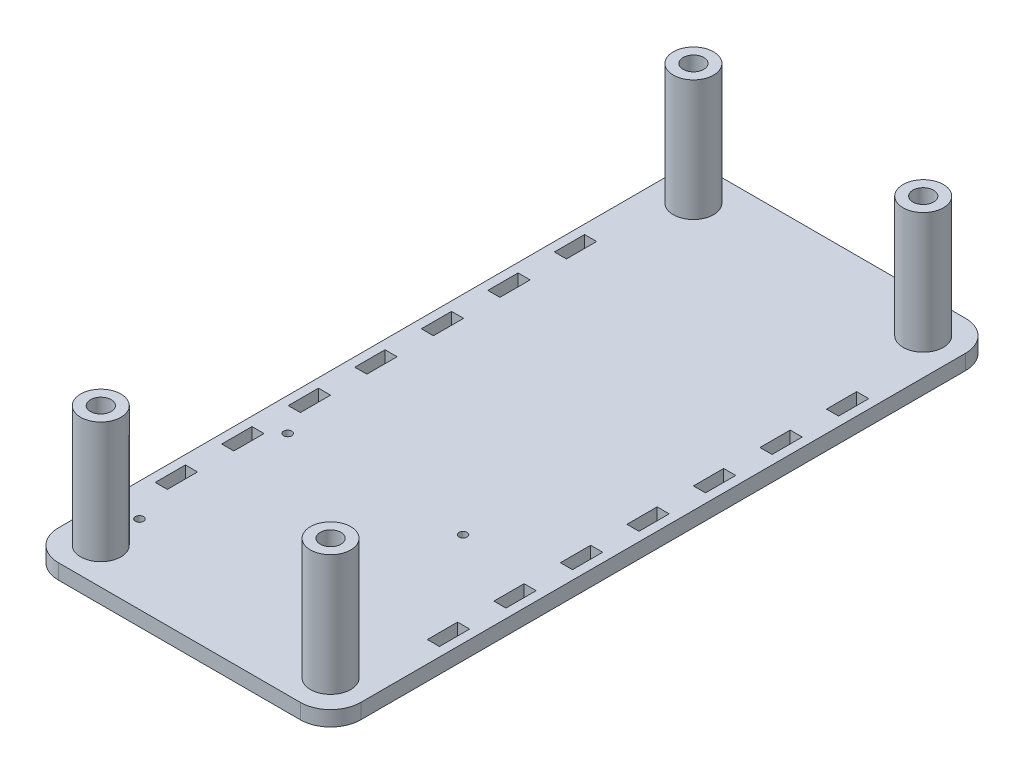
SolidWorks part; units mm, degrees
ref_plane "Front Plane" through (0, 0, 0) normal (0, 0, 1) x (1, 0, 0)
ref_plane "Top Plane" through (0, 0, 0) normal (0, 1, 0) x (1, 0, 0)
ref_plane "Right Plane" through (0, 0, 0) normal (1, 0, 0) x (0, 0, -1)
sketch "Sketch1" plane through (0, 0, 0) normal (0, 1, 0) x (1, 0, 0)
  line L2 (-104.5, 110) -> (-4.5, 110)
  line L5 (-104.5, 110) -> (-104.5, -110)
  line L6 (-104.5, -110) -> (-4.5, -110)
  line L7 (-4.5, 110) -> (-4.5, -110)
  point P6 (-54.5, 110)
  dimension "D1" = 220
  dimension "D2" = 100
extrude "Boss-Extrude1" add sketch "Sketch1" along normal blind 5
fillet "Fillet1" radius 10 1 edges at (-4.5, 2.5, 110)
fillet "Fillet2" radius 10 1 edges at (-4.5, 2.5, -110)
fillet "Fillet3" radius 10 1 edges at (-104.5, 2.5, 110)
fillet "Fillet4" radius 10 1 edges at (-104.5, 2.5, -110)
sketch "Sketch2" plane through (0, 5, 0) normal (0, 1, 0) x (1, 0, 0)
  circle A0 centre (-92.5, 98) radius 6.6681
  circle A1 centre (-92.5, -98) radius 6.6681
  circle A2 centre (-16.5, 98) radius 6.6681
  circle A3 centre (-16.5, -98) radius 6.6681
  point P17 (-54.5, 0)
extrude "Boss-Extrude2" add sketch "Sketch2" along normal blind 40
sketch "Sketch4" plane through (0, 45, 0) normal (0, 1, 0) x (1, 0, 0)
  circle A2 centre (-92.5, 98) radius 3.4181
  circle A3 centre (-92.5, 98) radius 3.4181
  dimension "D1" = 3.25
extrude "Cut-Extrude1" cut sketch "Sketch4" against normal blind 15
sketch "Sketch5" plane through (0, 45, 0) normal (0, 1, 0) x (1, 0, 0)
  circle A2 centre (-92.5, -98) radius 3.4181
  circle A3 centre (-92.5, -98) radius 3.4181
  dimension "D1" = 3.25
extrude "Cut-Extrude2" cut sketch "Sketch5" against normal blind 15
sketch "Sketch6" plane through (0, 45, 0) normal (0, 1, 0) x (1, 0, 0)
  circle A2 centre (-16.5, 98) radius 3.4181
  circle A3 centre (-16.5, 98) radius 3.4181
  dimension "D1" = 3.25
extrude "Cut-Extrude3" cut sketch "Sketch6" against normal blind 15
sketch "Sketch7" plane through (0, 45, 0) normal (0, 1, 0) x (1, 0, 0)
  circle A2 centre (-16.5, -98) radius 3.4181
  circle A3 centre (-16.5, -98) radius 3.4181
  dimension "D1" = 3.25
extrude "Cut-Extrude4" cut sketch "Sketch7" against normal blind 15
sketch "Sketch8" plane through (0, 5, 0) normal (0, 1, 0) x (1, 0, 0)
  line L0 (-7.5, -71) -> (-11.5, -71) construction
  line L1 (-24.75, 0) -> (24.75, 0) construction
  line L2 (-11.5, -71) -> (-11.5, -61) construction
  line L3 (-7.5, 5) -> (-11.5, 5) construction
  line L9 (-101.5, 71) -> (-97.5, 71) construction
  line L14 (-97.5, 71) -> (-97.5, 61) construction
  line L15 (-7.5, -5) -> (-11.5, -5) construction
  line L19 (-101.5, 71) -> (-97.5, 71)
  line L20 (-101.5, 71) -> (-101.5, 61)
  line L21 (-101.5, 61) -> (-97.5, 61)
  line L22 (-97.5, 71) -> (-97.5, 61)
  line L24 (-101.5, 49) -> (-97.5, 49)
  line L25 (-97.5, 39) -> (-97.5, 49)
  line L26 (-101.5, 39) -> (-97.5, 39)
  line L27 (-101.5, 39) -> (-101.5, 49)
  line L28 (-11.5, -5) -> (-11.5, 5) construction
  line L33 (-97.5, -5) -> (-97.5, 5) construction
  line L34 (-101.5, -5) -> (-97.5, -5) construction
  line L37 (-101.5, 27) -> (-101.5, 17)
  line L38 (-101.5, 27) -> (-97.5, 27)
  line L39 (-97.5, 27) -> (-97.5, 17)
  line L40 (-101.5, 17) -> (-97.5, 17)
  line L41 (-97.5, -5) -> (-97.5, 5)
  line L42 (-101.5, 5) -> (-97.5, 5)
  line L43 (-101.5, -5) -> (-101.5, 5)
  line L44 (-101.5, -5) -> (-97.5, -5)
  line L45 (-11.5, 71) -> (-11.5, 61) construction
  line L46 (-101.5, 5) -> (-97.5, 5) construction
  line L47 (-7.5, 71) -> (-11.5, 71) construction
  line L48 (-7.5, -71) -> (-11.5, -71)
  line L49 (-7.5, -71) -> (-7.5, -61)
  line L50 (-7.5, -61) -> (-11.5, -61)
  line L51 (-11.5, -71) -> (-11.5, -61)
  line L52 (-7.5, -49) -> (-11.5, -49)
  line L53 (-97.5, -71) -> (-97.5, -61) construction
  line L54 (-101.5, -71) -> (-97.5, -71) construction
  line L55 (-11.5, -39) -> (-11.5, -49)
  line L56 (-7.5, -39) -> (-11.5, -39)
  line L59 (-101.5, -17) -> (-97.5, -17)
  line L60 (-97.5, -27) -> (-97.5, -17)
  line L61 (-101.5, -27) -> (-97.5, -27)
  line L62 (-101.5, -27) -> (-101.5, -17)
  line L63 (-101.5, -39) -> (-101.5, -49)
  line L64 (-101.5, -39) -> (-97.5, -39)
  line L65 (-97.5, -39) -> (-97.5, -49)
  line L66 (-101.5, -49) -> (-97.5, -49)
  line L67 (-97.5, -71) -> (-97.5, -61)
  line L68 (-101.5, -61) -> (-97.5, -61)
  line L69 (-101.5, -71) -> (-101.5, -61)
  line L70 (-101.5, -71) -> (-97.5, -71)
  line L71 (-7.5, -39) -> (-7.5, -49)
  line L72 (-7.5, -27) -> (-7.5, -17)
  line L73 (-7.5, -27) -> (-11.5, -27)
  line L74 (-11.5, -27) -> (-11.5, -17)
  line L75 (-7.5, -17) -> (-11.5, -17)
  line L76 (-7.5, -5) -> (-11.5, -5)
  line L77 (-7.5, 5) -> (-11.5, 5)
  line L79 (-7.5, -5) -> (-7.5, 5)
  line L81 (-11.5, -5) -> (-11.5, 5)
  line L82 (-7.5, 17) -> (-11.5, 17)
  line L83 (-11.5, 27) -> (-11.5, 17)
  line L84 (-7.5, 27) -> (-11.5, 27)
  line L85 (-7.5, 27) -> (-7.5, 17)
  line L86 (-7.5, 39) -> (-7.5, 49)
  line L87 (-7.5, 39) -> (-11.5, 39)
  line L88 (-11.5, 39) -> (-11.5, 49)
  line L89 (-7.5, 49) -> (-11.5, 49)
  line L90 (-11.5, 71) -> (-11.5, 61)
  line L91 (-7.5, 61) -> (-11.5, 61)
  line L92 (-7.5, 71) -> (-7.5, 61)
  line L93 (-7.5, 71) -> (-11.5, 71)
extrude "Cut-Extrude5" cut sketch "Sketch8" against normal through all
sketch "Sketch9" plane through (0, 0, 0) normal (0, -1, 0) x (1, 0, 0)
  circle A0 centre (-93.6228, 35.0733) radius 1.35
  circle A1 centre (-35.6228, 35.0733) radius 1.35
  circle A2 centre (-35.6228, 84.0733) radius 1.35
  circle A3 centre (-93.6228, 84.0733) radius 1.35
  point P0 (0, 0)
extrude "Cut-Extrude7" cut sketch "Sketch9" against normal through all
